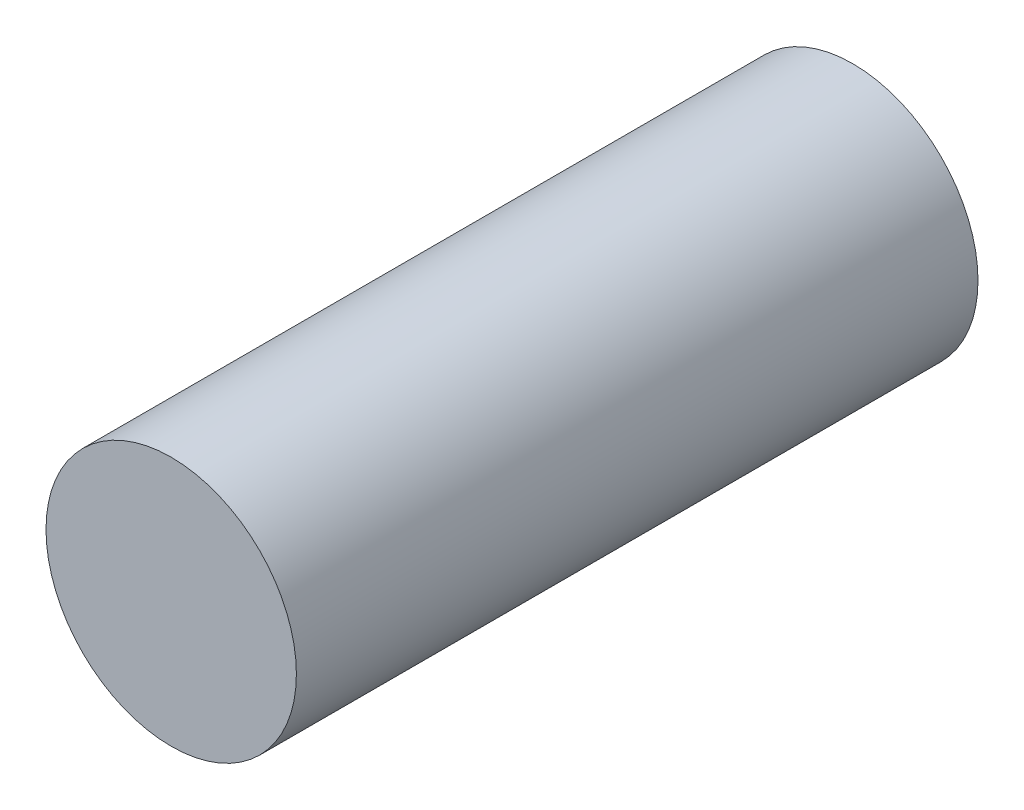
SolidWorks part; units mm, degrees
ref_plane "Front Plane" through (0, 0, 0) normal (0, 0, 1) x (1, 0, 0)
ref_plane "Top Plane" through (0, 0, 0) normal (0, 1, 0) x (1, 0, 0)
ref_plane "Right Plane" through (0, 0, 0) normal (1, 0, 0) x (0, 0, -1)
sketch "Sketch1" plane through (0, 0, 0) normal (0, 0, 1) x (1, 0, 0)
  circle A0 centre (0, 0) radius 18
  dimension "D1" = 36
extrude "Boss-Extrude1" add sketch "Sketch1" along normal blind 98
